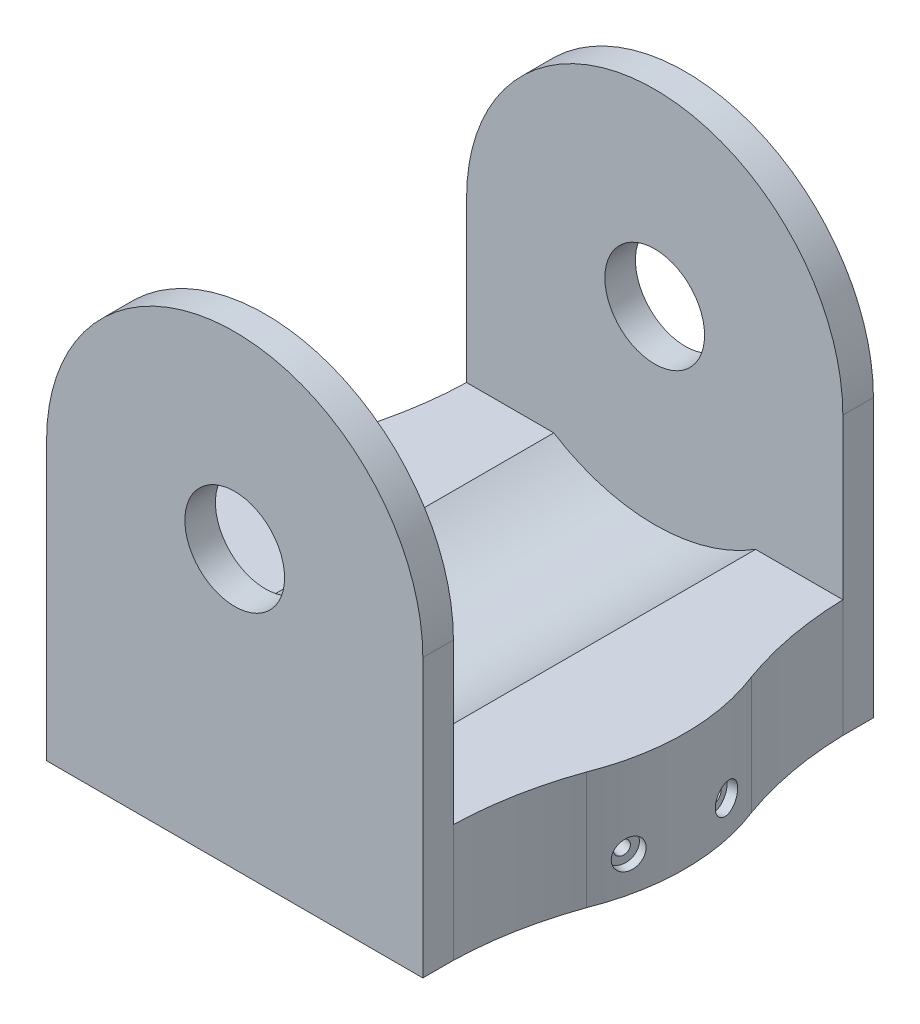
SolidWorks part; units mm, degrees
ref_plane "Front Plane" through (0, 0, 0) normal (0, 0, 1) x (1, 0, 0)
ref_plane "Top Plane" through (0, 0, 0) normal (0, 1, 0) x (1, 0, 0)
ref_plane "Right Plane" through (0, 0, 0) normal (1, 0, 0) x (0, 0, -1)
sketch "Sketch1" plane through (0, 0, 0) normal (0, 1, 0) x (1, 0, 0)
  circle A0 centre (0, 0) radius 41.5
  circle A1 centre (0, 0) radius 47.8
  dimension "D1" = 83
  dimension "D2" = 6.3
extrude "Cap base" add sketch "Sketch1" along normal blind 15
sketch "Sketch2" plane through (0, 15, 0) normal (0, 1, 0) x (1, 0, 0)
  circle A0 centre (0, 0) radius 47.8 construction
  circle A1 centre (0, 0) radius 47.8
extrude "Cap top" add sketch "Sketch2" along normal blind 10
sketch "Sketch3" plane through (0, 0, 0) normal (0, 0, 1) x (1, 0, 0)
  line L0 (-41.5, 15) -> (41.5, 15) construction
  line L1 (-40, 59) -> (-40, 0)
  line L2 (-47.8, 0) -> (47.8, 0) construction
  line L3 (40, 59) -> (40, 0)
  line L4 (40, 0) -> (-40, 0)
  arc A0 (40, 59) -> (-40, 59) centre (0, 59) ccw
  dimension "D1" = 80
  dimension "D2" = 44
  dimension "D3" = 59
extrude "Sides" add sketch "Sketch3" along normal blind 6.5 from offset 41.4
sketch "Sketch4" plane through (0, 25, 0) normal (0, 1, 0) x (1, 0, 0)
  line L1 (40, -41.4) -> (-40, -41.4) construction
  line L2 (0, -55) -> (0, 55) construction
  line L3 (40, -41.4) -> (23.8931, -41.4)
  line L4 (-23.8931, -41.4) -> (-40, -41.4)
  arc A0 (-40, -41.4) -> (-45.1045, -15.8247) centre (-116.4461, -43.3607) ccw
  arc A1 (23.8931, -41.4) -> (-23.8931, -41.4) centre (0, 0) ccw construction
  arc A2 (40, -41.4) -> (45.1045, -15.8247) centre (116.4461, -43.3607) cw
  arc A3 (23.8931, -41.4) -> (45.1045, -15.8247) centre (0, 0) ccw
  arc A4 (-45.1045, -15.8247) -> (-23.8931, -41.4) centre (0, 0) ccw
  arc M1 (23.8931, -41.4) -> (-23.8931, -41.4) centre (0, 0) ccw
  dimension "D1" = 25.5753
  dimension "D2" = 76.4712
extrude "Sides to cap" add sketch "Sketch4" against normal blind 25 contours A0 L4 M1 | L3 A2 M1
mirror "Mirror1" about plane through (0, 0, 0) normal (0, 0, 1) of "Sides to cap"
mirror "Mirror sides" about plane through (0, 0, 0) normal (0, 0, 1) of "Sides"
sketch "Sketch5" plane through (0, 0, 41.4) normal (0, 0, -1) x (-1, 0, 0)
  circle A0 centre (0, 59) radius 40.2
  dimension "D1" = 80.4
extrude "Tracks for housing" cut sketch "Sketch5" along normal blind 45
mirror "Mirror tracks" about plane through (0, 0, 0) normal (0, 0, 1) of "Tracks for housing"
sketch "Sketch6" plane through (0, 0, 47.9) normal (0, 0, 1) x (1, 0, 0)
  circle A0 centre (0, 59) radius 10.6
  dimension "D1" = 21.2
extrude "Hole for gear shafts" cut sketch "Sketch6" against normal through all
ref_plane "Plane3" through (44.4696, 0, -17.5298) normal (0.9303, 0, -0.3667) x (-0.3667, 0, -0.9303)
sketch "Sketch8" plane through (44.4696, 0, -17.5298) normal (0.9303, 0, -0.3667) x (-0.3667, 0, -0.9303)
  line L0 (0, 0) -> (0, 25) construction
  circle A0 centre (0, 12.5) radius 1.5
  dimension "D1" = 3
ref_plane "Plane4" through (46.7348, 0, -10.035) normal (0.9777, 0, -0.2099) x (-0.2099, 0, -0.9777)
sketch "Sketch9" plane through (46.7348, 0, -10.035) normal (0.9777, 0, -0.2099) x (-0.2099, 0, -0.9777)
  line L0 (-26.475, 0) -> (7.8033, 0) construction
  circle A0 centre (0, 7.5) radius 1.5
  dimension "D1" = 3
  dimension "D3" = 7.5
  dimension "D2" = 7.5
extrude "Cut-Extrude2" cut sketch "Sketch9" against normal blind 10
pattern_circular "CirPattern1" count 2 over 25 about axis through (0, 15, 0) along (0, -1, 0) of "Cut-Extrude2"
mirror "Mirror2" about plane through (0, 0, 0) normal (1, 0, 0) of "CirPattern1", "Cut-Extrude2"
sketch "Sketch10" plane through (46.7348, 0, -10.035) normal (0.9777, 0, -0.2099) x (-0.2099, 0, -0.9777)
  circle A2 centre (0, 7.5) radius 3.1
  circle A3 centre (0, 7.5) radius 3.1
  dimension "D1" = 1.6
extrude "Cut-Extrude3" cut sketch "Sketch10" against normal blind 2
pattern_circular "CirPattern2" count 2 over 25 about axis through (0, 15, 0) along (0, -1, 0) of "Cut-Extrude3"
mirror "Mirror3" about plane through (0, 0, 0) normal (1, 0, 0) of "CirPattern2", "Cut-Extrude3"
equation "\"D2@Sketch3\"=\"D1@Sketch3\"/2+4"
equation "\"D3@Sketch3\"=\"D2@Sketch3\"+15"
